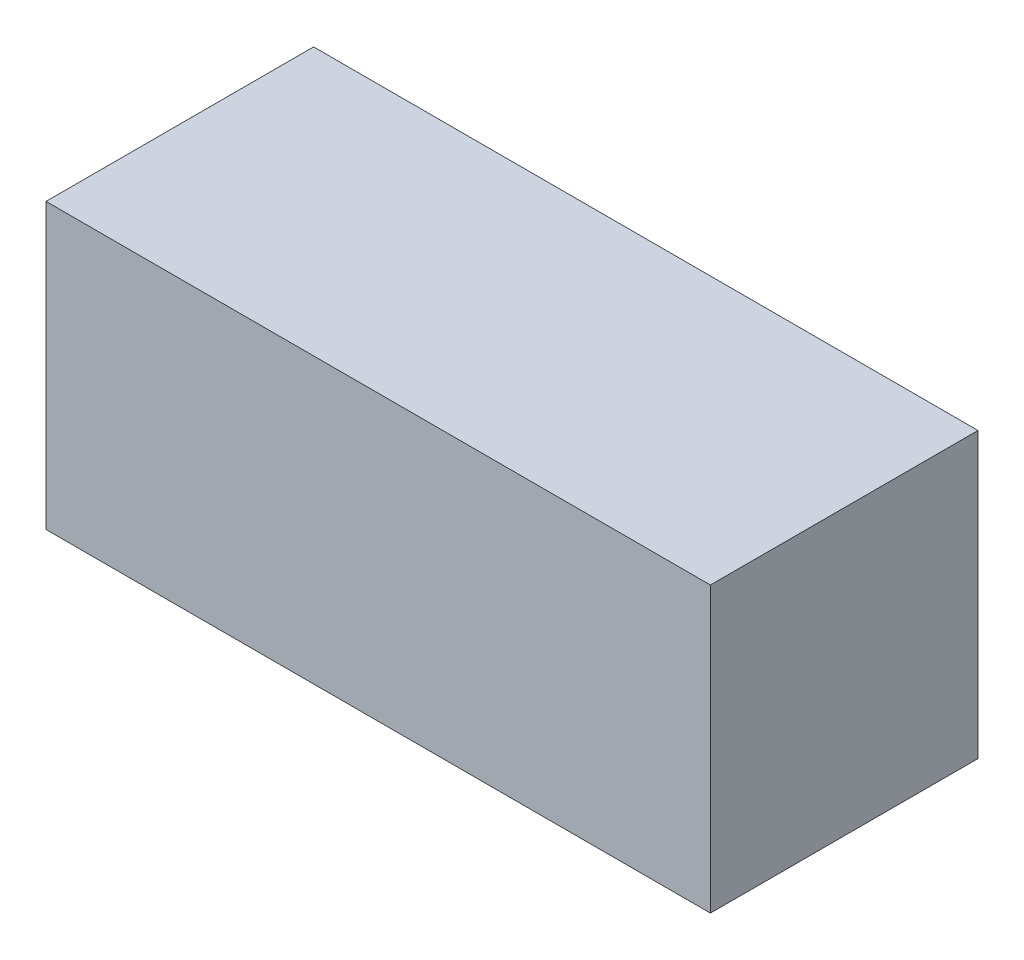
SolidWorks part; units mm, degrees
ref_plane "Front Plane" through (0, 0, 0) normal (0, 0, 1) x (1, 0, 0)
ref_plane "Top Plane" through (0, 0, 0) normal (0, 1, 0) x (1, 0, 0)
ref_plane "Right Plane" through (0, 0, 0) normal (1, 0, 0) x (0, 0, -1)
sketch "Sketch1" plane through (0, 0, 0) normal (0, 1, 0) x (1, 0, 0)
  line L1 (0, 0) -> (6058, 0)
  line L2 (0, 0) -> (0, 2440)
  line L3 (0, 2440) -> (6058, 2440)
  line L4 (6058, 0) -> (6058, 2440)
  dimension "D1" = 6058
  dimension "D2" = 2440
extrude "Boss-Extrude1" add sketch "Sketch1" along normal blind 2591
ref_plane "Plane-Mid-Length" through (0, 0, -1220) normal (0, 0, 1) x (1, 0, 0)
ref_plane "Plane-Mid-Width" through (3029, 0, 0) normal (-1, 0, 0) x (0, 0, 1)
ref_plane "Top of Corrugation" through (0, 2471, 0) normal (0, 1, 0) x (1, 0, 0)
ref_plane "Bottom of Corrugation" through (0, 111, 0) normal (0, 1, 0) x (1, 0, 0)
sketch "Sketch4" plane through (0, 2591, 0) normal (0, 1, 0) x (1, 0, 0)
  line L0 (6058, 2440) -> (5884, 2440)
  line L1 (6058, 2440) -> (0, 2440) construction
  line L2 (5884, 2440) -> (5884, 2404)
  line L3 (5884, 2404) -> (5774, 2404)
  line L4 (5774, 2404) -> (5706, 2440)
  line L5 (5706, 2440) -> (5634, 2440)
  line L6 (5634, 2440) -> (5566, 2404)
  line L7 (5566, 2404) -> (5496, 2404)
  line L8 (5496, 2404) -> (5428, 2440)
  line L9 (5428, 2440) -> (5356, 2440)
  line L10 (5356, 2440) -> (5288, 2404)
  line L11 (5288, 2404) -> (5218, 2404)
  line L12 (5218, 2404) -> (5150, 2440)
  line L13 (5150, 2440) -> (5078, 2440)
  line L14 (5078, 2440) -> (5010, 2404)
  line L15 (5010, 2404) -> (4940, 2404)
  line L16 (4940, 2404) -> (4872, 2440)
  line L17 (4872, 2440) -> (4800, 2440)
  line L18 (4800, 2440) -> (4732, 2404)
  line L19 (4732, 2404) -> (4662, 2404)
  line L20 (4662, 2404) -> (4594, 2440)
  line L21 (4594, 2440) -> (4522, 2440)
  line L22 (4522, 2440) -> (4454, 2404)
  line L23 (4454, 2404) -> (4384, 2404)
  line L24 (4384, 2404) -> (4316, 2440)
  line L25 (4316, 2440) -> (4244, 2440)
  line L26 (4244, 2440) -> (4176, 2404)
  line L27 (4176, 2404) -> (4106, 2404)
  line L28 (4106, 2404) -> (4038, 2440)
  line L29 (4038, 2440) -> (3966, 2440)
  line L30 (3966, 2440) -> (3898, 2404)
  line L31 (3898, 2404) -> (3828, 2404)
  line L32 (3828, 2404) -> (3760, 2440)
  line L33 (3760, 2440) -> (3688, 2440)
  line L34 (3688, 2440) -> (3620, 2404)
  line L35 (3620, 2404) -> (3550, 2404)
  line L36 (3550, 2404) -> (3482, 2440)
  line L37 (3482, 2440) -> (3410, 2440)
  line L38 (3410, 2440) -> (3342, 2404)
  line L39 (3342, 2404) -> (3272, 2404)
  line L40 (3272, 2404) -> (3204, 2440)
  line L41 (3204, 2440) -> (3132, 2440)
  line L42 (3132, 2440) -> (3064, 2404)
  line L43 (3064, 2404) -> (2994, 2404)
  line L44 (2994, 2404) -> (2926, 2440)
  line L45 (2926, 2440) -> (2854, 2440)
  line L46 (2854, 2440) -> (2786, 2404)
  line L47 (2786, 2404) -> (2716, 2404)
  line L48 (2716, 2404) -> (2648, 2440)
  line L49 (2648, 2440) -> (2576, 2440)
  line L50 (2576, 2440) -> (2508, 2404)
  line L51 (2508, 2404) -> (2438, 2404)
  line L52 (2438, 2404) -> (2370, 2440)
  line L53 (2370, 2440) -> (2298, 2440)
  line L54 (2298, 2440) -> (2230, 2404)
  line L55 (2230, 2404) -> (2160, 2404)
  line L56 (2160, 2404) -> (2092, 2440)
  line L57 (2092, 2440) -> (2020, 2440)
  line L58 (2020, 2440) -> (1952, 2404)
  line L59 (1952, 2404) -> (1882, 2404)
  line L60 (1882, 2404) -> (1814, 2440)
  line L61 (1814, 2440) -> (1742, 2440)
  line L62 (1742, 2440) -> (1674, 2404)
  line L63 (1674, 2404) -> (1604, 2404)
  line L64 (1604, 2404) -> (1536, 2440)
  line L65 (1536, 2440) -> (1464, 2440)
  line L66 (1464, 2440) -> (1396, 2404)
  line L67 (1396, 2404) -> (1326, 2404)
  line L68 (1326, 2404) -> (1258, 2440)
  line L69 (1258, 2440) -> (1186, 2440)
  line L70 (1186, 2440) -> (1118, 2404)
  line L71 (1118, 2404) -> (1048, 2404)
  line L72 (1048, 2404) -> (980, 2440)
  line L73 (980, 2440) -> (908, 2440)
  line L74 (908, 2440) -> (840, 2404)
  line L75 (840, 2404) -> (770, 2404)
  line L76 (770, 2404) -> (702, 2440)
  line L77 (702, 2440) -> (630, 2440)
  line L78 (630, 2440) -> (562, 2404)
  line L79 (562, 2404) -> (492, 2404)
  line L80 (492, 2404) -> (424, 2440)
  line L81 (0, 2440) -> (174, 2440)
  line L82 (174, 2440) -> (174, 2404)
  line L83 (174, 2404) -> (284, 2404)
  line L84 (284, 2404) -> (352, 2440)
  line L85 (352, 2440) -> (424, 2440)
  line L86 (-1425.05, 1220) -> (1425.05, 1220) construction
  line L87 (352, 0) -> (424, 0)
  line L88 (284, 36) -> (352, 0)
  line L89 (174, 36) -> (284, 36)
  line L90 (174, 0) -> (174, 36)
  line L91 (0, 0) -> (174, 0)
  line L92 (492, 36) -> (424, 0)
  line L93 (562, 36) -> (492, 36)
  line L94 (630, 0) -> (562, 36)
  line L95 (702, 0) -> (630, 0)
  line L96 (770, 36) -> (702, 0)
  line L97 (840, 36) -> (770, 36)
  line L98 (908, 0) -> (840, 36)
  line L99 (980, 0) -> (908, 0)
  line L100 (1048, 36) -> (980, 0)
  line L101 (1118, 36) -> (1048, 36)
  line L102 (1186, 0) -> (1118, 36)
  line L103 (1258, 0) -> (1186, 0)
  line L104 (1326, 36) -> (1258, 0)
  line L105 (1396, 36) -> (1326, 36)
  line L106 (1464, 0) -> (1396, 36)
  line L107 (1536, 0) -> (1464, 0)
  line L108 (1604, 36) -> (1536, 0)
  line L109 (1674, 36) -> (1604, 36)
  line L110 (1742, 0) -> (1674, 36)
  line L111 (1814, 0) -> (1742, 0)
  line L112 (1882, 36) -> (1814, 0)
  line L113 (1952, 36) -> (1882, 36)
  line L114 (2020, 0) -> (1952, 36)
  line L115 (2092, 0) -> (2020, 0)
  line L116 (2160, 36) -> (2092, 0)
  line L117 (2230, 36) -> (2160, 36)
  line L118 (2298, 0) -> (2230, 36)
  line L119 (2370, 0) -> (2298, 0)
  line L120 (2438, 36) -> (2370, 0)
  line L121 (2508, 36) -> (2438, 36)
  line L122 (2576, 0) -> (2508, 36)
  line L123 (2648, 0) -> (2576, 0)
  line L124 (2716, 36) -> (2648, 0)
  line L125 (2786, 36) -> (2716, 36)
  line L126 (2854, 0) -> (2786, 36)
  line L127 (2926, 0) -> (2854, 0)
  line L128 (2994, 36) -> (2926, 0)
  line L129 (3064, 36) -> (2994, 36)
  line L130 (3132, 0) -> (3064, 36)
  line L131 (3204, 0) -> (3132, 0)
  line L132 (3272, 36) -> (3204, 0)
  line L133 (3342, 36) -> (3272, 36)
  line L134 (3410, 0) -> (3342, 36)
  line L135 (3482, 0) -> (3410, 0)
  line L136 (3550, 36) -> (3482, 0)
  line L137 (3620, 36) -> (3550, 36)
  line L138 (3688, 0) -> (3620, 36)
  line L139 (3760, 0) -> (3688, 0)
  line L140 (3828, 36) -> (3760, 0)
  line L141 (3898, 36) -> (3828, 36)
  line L142 (3966, 0) -> (3898, 36)
  line L143 (4038, 0) -> (3966, 0)
  line L144 (4106, 36) -> (4038, 0)
  line L145 (4176, 36) -> (4106, 36)
  line L146 (4244, 0) -> (4176, 36)
  line L147 (4316, 0) -> (4244, 0)
  line L148 (4384, 36) -> (4316, 0)
  line L149 (4454, 36) -> (4384, 36)
  line L150 (4522, 0) -> (4454, 36)
  line L151 (4594, 0) -> (4522, 0)
  line L152 (4662, 36) -> (4594, 0)
  line L153 (4732, 36) -> (4662, 36)
  line L154 (4800, 0) -> (4732, 36)
  line L155 (4872, 0) -> (4800, 0)
  line L156 (4940, 36) -> (4872, 0)
  line L157 (5010, 36) -> (4940, 36)
  line L158 (5078, 0) -> (5010, 36)
  line L159 (5150, 0) -> (5078, 0)
  line L160 (5218, 36) -> (5150, 0)
  line L161 (5288, 36) -> (5218, 36)
  line L162 (5356, 0) -> (5288, 36)
  line L163 (5428, 0) -> (5356, 0)
  line L164 (5496, 36) -> (5428, 0)
  line L165 (5566, 36) -> (5496, 36)
  line L166 (5634, 0) -> (5566, 36)
  line L167 (5706, 0) -> (5634, 0)
  line L168 (5774, 36) -> (5706, 0)
  line L169 (5884, 36) -> (5774, 36)
  line L170 (5884, 0) -> (5884, 36)
  line L171 (6058, 0) -> (5884, 0)
  line L172 (6058, 2440) -> (6058, 2280)
  line L173 (6058, 0) -> (6058, 2440) construction
  line L174 (6058, 2280) -> (6003, 2280)
  line L175 (6003, 2280) -> (6003, 2168)
  line L176 (6003, 2168) -> (6058, 2150)
  line L177 (6058, 2150) -> (6058, 2040)
  line L178 (6058, 2040) -> (6003, 2022)
  line L179 (6003, 2022) -> (6003, 1918)
  line L180 (6003, 1918) -> (6058, 1900)
  line L181 (6058, 1900) -> (6058, 1790)
  line L182 (6058, 1790) -> (6003, 1772)
  line L183 (6003, 1772) -> (6003, 1668)
  line L184 (6003, 1668) -> (6058, 1650)
  line L185 (6058, 1650) -> (6058, 1540)
  line L186 (6058, 1540) -> (6003, 1522)
  line L187 (6003, 1522) -> (6003, 1418)
  line L188 (6003, 1418) -> (6058, 1400)
  line L189 (6058, 1400) -> (6058, 1290)
  line L190 (6058, 1290) -> (6003, 1272)
  line L191 (6003, 1272) -> (6003, 1168)
  line L192 (6003, 1168) -> (6058, 1150)
  line L193 (6058, 1150) -> (6058, 1040)
  line L194 (6058, 1040) -> (6003, 1022)
  line L195 (6003, 1022) -> (6003, 918)
  line L196 (6003, 918) -> (6058, 900)
  line L197 (6058, 900) -> (6058, 790)
  line L198 (6058, 790) -> (6003, 772)
  line L199 (6003, 772) -> (6003, 668)
  line L200 (6003, 668) -> (6058, 650)
  line L201 (6058, 650) -> (6058, 540)
  line L202 (6058, 540) -> (6003, 522)
  line L203 (6003, 522) -> (6003, 418)
  line L204 (6058, 0) -> (6058, 160)
  line L205 (6058, 160) -> (6003, 160)
  line L206 (6003, 160) -> (6003, 272)
  line L207 (6003, 272) -> (6058, 290)
  line L208 (6058, 290) -> (6058, 400)
  line L209 (6058, 400) -> (6003, 418)
  dimension "D1" = 174
  dimension "D2" = 36
  dimension "D3" = 36
  dimension "D4" = 72
  dimension "D5" = 68
  dimension "D6" = 68
  dimension "D7" = 70
  dimension "D8" = 68
  dimension "D9" = 110
  dimension "D11" = 174
  dimension "D12" = 72
  dimension "D13" = 68
  dimension "D14" = 160
  dimension "D15" = 160
  dimension "D16" = 55
  dimension "D17" = 112
  dimension "D18" = 18
  dimension "D19" = 18
  dimension "D20" = 110
  dimension "D21" = 104
  dimension "D23" = 18
  dimension "D24" = 18
  dimension "D25" = 110
  dimension "D10" = 19
  dimension "D22" = 7
